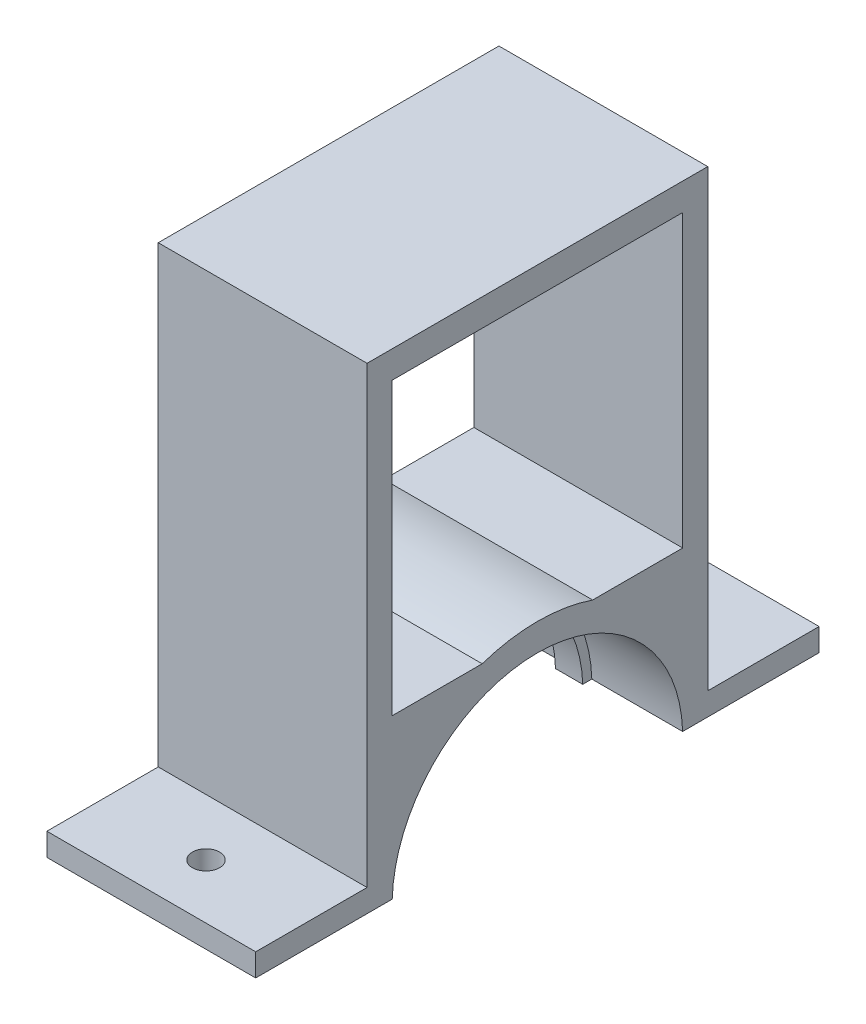
SolidWorks part; units mm, degrees
ref_plane "Front Plane" through (0, 0, 0) normal (0, 0, 1) x (1, 0, 0)
ref_plane "Top Plane" through (0, 0, 0) normal (0, 1, 0) x (1, 0, 0)
ref_plane "Right Plane" through (0, 0, 0) normal (1, 0, 0) x (0, 0, -1)
sketch "Sketch2" plane through (0, 0, 0) normal (0, 1, 0) x (1, 0, 0)
  line L0 (-71.7222, 0) -> (83.9696, 0) construction
  line L1 (-11.5, 16) -> (-1.5, 16)
  line L2 (-1.5, 16) -> (-1.5, 15)
  line L3 (-1.5, 15) -> (1.5, 15)
  line L4 (0, 51.3789) -> (0, -38.4859) construction
  line L5 (-11.5, 16) -> (-11.5, 19)
  line L6 (-11.5, 19) -> (11.5, 19)
  line L7 (11.5, 16) -> (11.5, 19)
  line L8 (1.5, 16) -> (1.5, 15)
  line L9 (11.5, 16) -> (1.5, 16)
  point P12 (0, 19)
  point P14 (0, 15)
  dimension "D1" = 16
  dimension "D2" = 15
  dimension "D3" = 1.5
  dimension "D4" = 10
  dimension "D5" = 3
revolve "Revolve1" add sketch "Sketch2" angle 360 about L0
sketch "Sketch3" plane through (0, 0, 0) normal (1, 0, 0) x (0, 0, -1)
  line L0 (-38.0691, 0) -> (35.3359, 0) construction
  line L1 (0, 27.1286) -> (0, -26.0041) construction
  line L2 (17.4601, -3) -> (31.0263, -3)
  line L3 (-17.4601, 3) -> (-31.0263, 3)
  line L4 (-17.4601, 3) -> (-17.4601, -3)
  line L5 (-17.4601, -3) -> (-31.0263, -3)
  line L6 (-31.0263, 3) -> (-31.0263, -3)
  line L7 (31.0263, 3) -> (31.0263, -3)
  line L8 (17.4601, 3) -> (31.0263, 3)
  line L9 (17.4601, 3) -> (17.4601, -3)
  dimension "D1" = 6
extrude "Boss-Extrude1" add sketch "Sketch3" along normal mid plane 23
sketch "Sketch4" plane through (0, 0, 0) normal (0, 1, 0) x (1, 0, 0)
  line L0 (-34.5056, 0) -> (37.3088, 0) construction
  circle A0 centre (0, 25) radius 1.5
  circle A1 centre (0, -25) radius 1.5
  dimension "D1" = 3
  dimension "D2" = 25
extrude "Cut-Extrude1" cut sketch "Sketch4" against normal mid plane 23
sketch "Sketch5" plane through (0, 0, 0) normal (1, 0, 0) x (0, 0, -1)
  line L0 (-44.9576, 0) -> (42.9868, 0) construction
  line L2 (-37.8752, -0.5) -> (37.8752, -0.5)
  line L3 (-37.8752, -0.5) -> (-37.8752, 0.5)
  line L4 (-37.8752, 0.5) -> (37.8752, 0.5)
  line L5 (37.8752, -0.5) -> (37.8752, 0.5)
  line L6 (-37.8752, -0.5) -> (37.8752, 0.5) construction
  line L7 (-37.8752, 0.5) -> (37.8752, -0.5) construction
  point P3 (0, 0)
  dimension "D1" = 1
extrude "Cut-Extrude2" cut sketch "Sketch5" against normal mid plane 52
delete or keep bodies "Body-Delete/Keep 3" type delete bodies bodies 104
sketch "Sketch7" plane through (0, 0, 0) normal (1, 0, 0) x (0, 0, -1)
  line L2 (-18.7617, 3) -> (-18.7617, 53)
  line L3 (-18.7617, 53) -> (18.7617, 53)
  line L4 (18.7617, 3) -> (18.7617, 53)
  line L5 (-16, 50) -> (16, 50)
  line L6 (-16, 50) -> (-16, 18)
  line L7 (-16, 18) -> (16, 18)
  line L8 (16, 50) -> (16, 18)
  line L9 (-16, 50) -> (16, 18) construction
  line L10 (-16, 18) -> (16, 50) construction
  arc A0 (18.7617, 3) -> (-18.7617, 3) centre (0, 0) ccw construction
  arc A1 (18.7617, 3) -> (-18.7617, 3) centre (0, 0) ccw
  point P5 (0, 0)
  point P7 (0, 34)
  point P13 (18.7617, 69.0077)
  dimension "D1" = 32
  dimension "D2" = 32
  dimension "D3" = 3
  dimension "D4" = 50
extrude "Boss-Extrude2" add sketch "Sketch7" along normal mid plane 23 contours A1 L4 L3 L2 L7 L6 L5 L8
